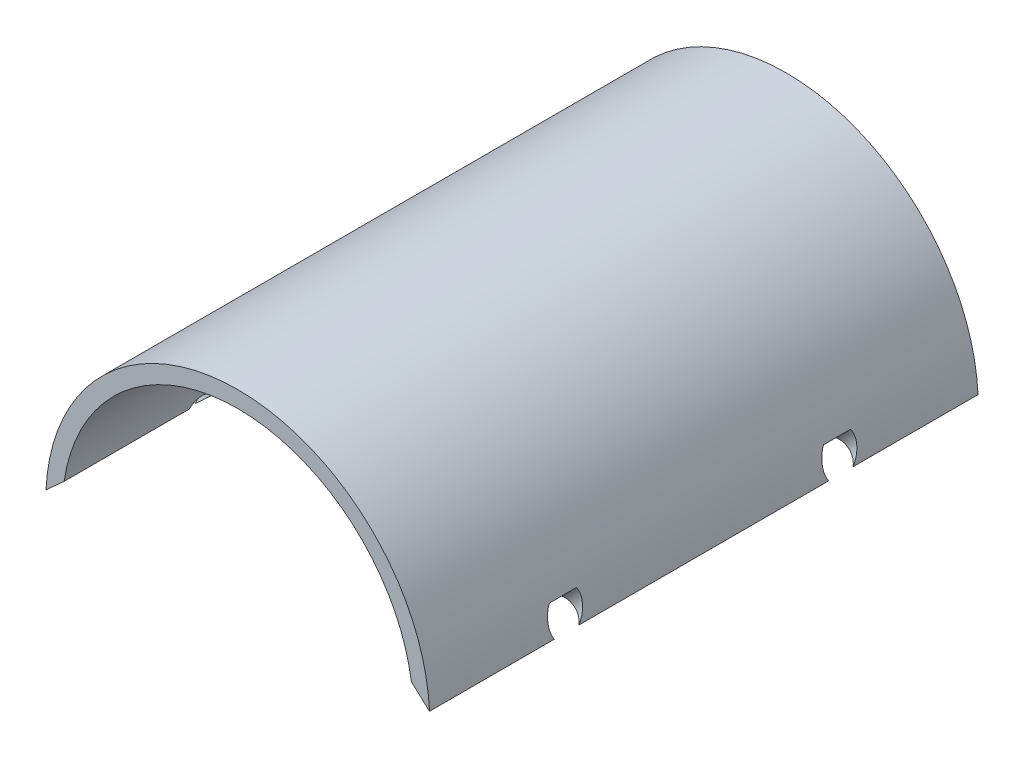
SolidWorks part; units mm, degrees
ref_plane "Front Plane" through (0, 0, 0) normal (0, 0, 1) x (1, 0, 0)
ref_plane "Top Plane" through (0, 0, 0) normal (0, 1, 0) x (1, 0, 0)
ref_plane "Right Plane" through (0, 0, 0) normal (1, 0, 0) x (0, 0, -1)
sketch "Sketch1" plane through (0, 0, 0) normal (0, 0, 1) x (1, 0, 0)
  line L0 (0, 0) -> (0, 44.45) construction
  line L1 (-40.2039, 5.9378) -> (40.2039, 5.9378) construction
  line L2 (-44.399, 2.1278) -> (44.399, 2.1278) construction
  line L3 (-40.2039, 5.9378) -> (-44.399, 2.1278)
  line L4 (40.2039, 5.9378) -> (44.399, 2.1278)
  arc A0 (44.399, 2.1278) -> (-44.399, 2.1278) centre (0, 0) ccw
  arc A1 (40.2039, 5.9378) -> (-40.2039, 5.9378) centre (0, 0) ccw
  dimension "D1" = 88.9
  dimension "D2" = 3.81
  dimension "D3" = 3.81
extrude "Boss-Extrude1" add sketch "Sketch1" along normal blind 127
sketch "Sketch2" plane through (-21.1272, 23.263, 0) normal (0.6723, -0.7403, 0) x (0.7403, 0.6723, 0)
  line L0 (-28.6033, 127) -> (-28.6033, 0) construction
  line L1 (-31.4368, 127) -> (-25.7698, 127) construction
  line L2 (-31.4368, 0) -> (-25.7698, 0) construction
  line L3 (-31.4368, 63.5) -> (-25.7698, 63.5) construction
  line L4 (-31.4368, 127) -> (-31.4368, 0) construction
  line L5 (-25.7698, 127) -> (-25.7698, 0) construction
  circle A0 centre (-28.6033, 95.25) radius 4
  circle A1 centre (-28.6033, 31.75) radius 4
  dimension "D1" = 8
  dimension "D2" = 31.75
extrude "Cut-Extrude1" cut sketch "Sketch2" against normal blind 2
sketch "Sketch3" plane through (21.1272, 23.263, 0) normal (-0.6723, -0.7403, 0) x (-0.7403, 0.6723, 0)
  line L0 (-28.6033, -127) -> (-28.6033, 0) construction
  line L1 (-25.7698, -127) -> (-31.4368, -127) construction
  line L2 (-25.7698, 0) -> (-31.4368, 0) construction
  line L3 (-25.7698, -63.5) -> (-31.4368, -63.5) construction
  line L4 (-25.7698, -127) -> (-25.7698, 0) construction
  line L5 (-31.4368, -127) -> (-31.4368, 0) construction
  circle A0 centre (-28.6033, -95.25) radius 4
  circle A1 centre (-28.6033, -31.75) radius 4
  dimension "D1" = 8
  dimension "D2" = 31.75
extrude "Cut-Extrude2" cut sketch "Sketch3" against normal blind 4.54
